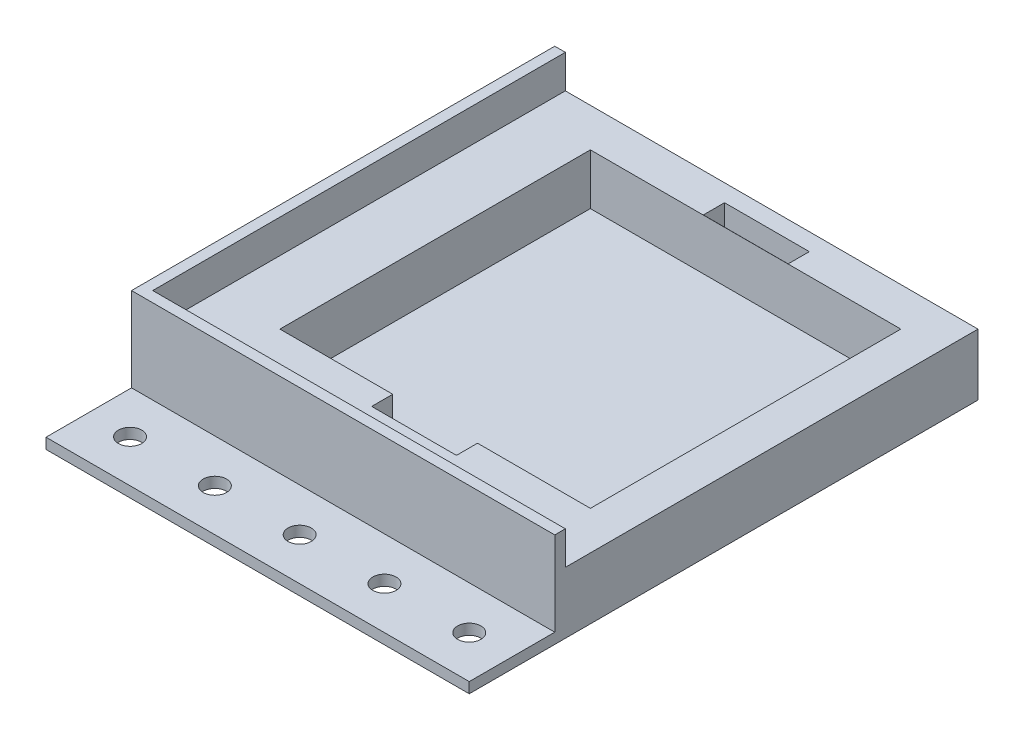
SolidWorks part; units mm, degrees
ref_plane "Front Plane" through (0, 0, 0) normal (0, 0, 1) x (1, 0, 0)
ref_plane "Top Plane" through (0, 0, 0) normal (0, 1, 0) x (1, 0, 0)
ref_plane "Right Plane" through (0, 0, 0) normal (1, 0, 0) x (0, 0, -1)
sketch "Sketch1" plane through (0, 0, 0) normal (0, 1, 0) x (1, 0, 0)
  line L1 (-152.4, -152.4) -> (152.4, -152.4)
  line L2 (-152.4, -152.4) -> (-152.4, 152.4)
  line L3 (-152.4, 152.4) -> (152.4, 152.4)
  line L4 (152.4, -152.4) -> (152.4, 152.4)
  line L5 (104.557, 11.557) -> (11.557, 11.557)
  line L6 (104.557, 11.557) -> (104.557, 104.557)
  line L7 (-11.557, 104.557) -> (-104.557, 104.557)
  line L8 (-11.557, 104.557) -> (-11.557, 11.557)
  line L9 (-11.557, 11.557) -> (-104.557, 11.557)
  line L10 (-104.557, 104.557) -> (-104.557, 11.557)
  line L11 (-11.557, 104.557) -> (-104.557, 11.557) construction
  line L12 (-11.557, 11.557) -> (-104.557, 104.557) construction
  line L13 (104.557, 104.557) -> (11.557, 104.557)
  line L14 (11.557, 11.557) -> (11.557, 104.557)
  line L15 (104.557, 11.557) -> (11.557, 104.557) construction
  line L16 (104.557, 104.557) -> (11.557, 11.557) construction
  line L17 (-104.557, -11.557) -> (-11.557, -11.557)
  line L18 (-104.557, -11.557) -> (-104.557, -104.557)
  line L19 (-104.557, -104.557) -> (-11.557, -104.557)
  line L20 (-11.557, -11.557) -> (-11.557, -104.557)
  line L21 (-104.557, -11.557) -> (-11.557, -104.557) construction
  line L22 (-104.557, -104.557) -> (-11.557, -11.557) construction
  line L23 (11.557, -11.557) -> (104.557, -11.557)
  line L24 (11.557, -11.557) -> (11.557, -104.557)
  line L25 (11.557, -104.557) -> (104.557, -104.557)
  line L26 (104.557, -11.557) -> (104.557, -104.557)
  line L27 (11.557, -11.557) -> (104.557, -104.557) construction
  line L28 (11.557, -104.557) -> (104.557, -11.557) construction
  point P0 (0, 0)
  point P6 (-58.057, 58.057)
  point P11 (58.057, 58.057)
  point P14 (0, 152.4)
  point P16 (-152.4, 0)
  point P18 (-58.057, -58.057)
  point P23 (58.057, -58.057)
  point P28 (-67.5261, -23.6543)
  point P29 (48.5879, -23.6543)
  point P30 (0, 0)
  point P31 (0, 0)
  point P32 (0, 0)
  point P33 (-55.8, 59.6413)
  point P34 (0, 0)
  point P35 (-104.557, 11.557)
  point P36 (0, 0)
  dimension "D1" = 93
  dimension "D2" = 304.8
  dimension "D3" = 23.114
  dimension "D4" = 23.114
extrude "Boss-Extrude1" add sketch "Sketch1" along normal blind 15.24
sketch "Sketch2" plane through (0, 0, 0) normal (0, -1, 0) x (-1, 0, 0)
  line L1 (152.4, -152.4) -> (-152.4, -152.4)
  line L2 (152.4, -152.4) -> (152.4, 152.4)
  line L3 (152.4, 152.4) -> (-152.4, 152.4)
  line L4 (-152.4, -152.4) -> (-152.4, 152.4)
extrude "Boss-Extrude2" add sketch "Sketch2" along normal blind 3.175
sketch "Sketch3" plane through (0, 15.24, 0) normal (0, 1, 0) x (1, 0, 0)
  line L0 (-104.557, 104.557) -> (-104.557, 11.557) construction
  line L1 (-152.4, -152.4) -> (152.4, -152.4)
  line L2 (-152.4, -152.4) -> (-152.4, 152.4)
  line L3 (-152.4, 152.4) -> (152.4, 152.4)
  line L4 (152.4, -152.4) -> (152.4, 152.4)
  line L5 (-123.607, -123.607) -> (123.607, -123.607)
  line L6 (-123.607, -123.607) -> (-123.607, 123.607)
  line L7 (-123.607, 123.607) -> (123.607, 123.607)
  line L8 (123.607, -123.607) -> (123.607, 123.607)
  line L9 (-11.557, 104.557) -> (-104.557, 104.557) construction
  line L10 (11.557, -104.557) -> (104.557, -104.557) construction
  line L11 (104.557, -104.557) -> (104.557, -11.557) construction
  dimension "D1" = 19.05
  dimension "D2" = 19.05
  dimension "D3" = 19.05
  dimension "D4" = 19.05
extrude "Boss-Extrude3" add sketch "Sketch3" along normal blind 10
sketch "Sketch4" plane through (0, 25.24, 0) normal (0, 1, 0) x (1, 0, 0)
  line L0 (123.607, 123.607) -> (-123.607, 123.607) construction
  line L1 (-126.782, 126.782) -> (126.782, 126.782)
  line L2 (-126.782, 126.782) -> (-126.782, -126.782)
  line L3 (-126.782, -126.782) -> (126.782, -126.782)
  line L4 (126.782, 126.782) -> (126.782, -126.782)
  line L5 (-123.607, 123.607) -> (-123.607, -123.607) construction
  line L6 (123.607, -123.607) -> (123.607, 123.607) construction
  line L7 (-123.607, -123.607) -> (123.607, -123.607) construction
  dimension "D1" = 3.175
  dimension "D2" = 3.175
  dimension "D3" = 3.175
  dimension "D4" = 3.175
extrude "Cut-Extrude1" cut sketch "Sketch4" against normal offset from surface (25.24 mm away) 3.175 flip side to cut up to face at (0, -3.175, 0)
sketch "Sketch5" plane through (0, 0, 0) normal (0, 1, 0) x (1, 0, 0)
  line L0 (152.4, -152.4) -> (-152.4, -152.4) construction
  line L1 (-152.4, -152.4) -> (-152.4, 152.4) construction
  circle A0 centre (-139.7, -139.7) radius 3.4925
  circle A1 centre (-114.3, -139.7) radius 3.4925
  circle A2 centre (-88.9, -139.7) radius 3.4925
  circle A3 centre (-63.5, -139.7) radius 3.4925
  circle A4 centre (-38.1, -139.7) radius 3.4925
  circle A5 centre (-12.7, -139.7) radius 3.4925
  circle A6 centre (12.7, -139.7) radius 3.4925
  circle A7 centre (38.1, -139.7) radius 3.4925
  circle A8 centre (63.5, -139.7) radius 3.4925
  circle A9 centre (88.9, -139.7) radius 3.4925
  circle A10 centre (114.3, -139.7) radius 3.4925
  circle A11 centre (139.7, -139.7) radius 3.4925
  circle A12 centre (-139.7, -114.3) radius 3.4925
  circle A13 centre (-139.7, -88.9) radius 3.4925
  circle A14 centre (-139.7, -63.5) radius 3.4925
  circle A15 centre (-139.7, -38.1) radius 3.4925
  circle A16 centre (-139.7, -12.7) radius 3.4925
  circle A17 centre (-139.7, 12.7) radius 3.4925
  circle A18 centre (-139.7, 38.1) radius 3.4925
  circle A19 centre (-139.7, 63.5) radius 3.4925
  circle A20 centre (-139.7, 88.9) radius 3.4925
  circle A21 centre (-139.7, 114.3) radius 3.4925
  circle A22 centre (-139.7, 139.7) radius 3.4925
  circle A23 centre (-114.3, 139.7) radius 3.4925
  circle A24 centre (-88.9, 139.7) radius 3.4925
  circle A25 centre (-63.5, 139.7) radius 3.4925
  circle A26 centre (-38.1, 139.7) radius 3.4925
  circle A27 centre (-12.7, 139.7) radius 3.4925
  circle A28 centre (12.7, 139.7) radius 3.4925
  circle A29 centre (38.1, 139.7) radius 3.4925
  circle A30 centre (63.5, 139.7) radius 3.4925
  circle A31 centre (88.9, 139.7) radius 3.4925
  circle A32 centre (114.3, 139.7) radius 3.4925
  circle A33 centre (139.7, 139.7) radius 3.4925
  circle A34 centre (139.7, 114.3) radius 3.4925
  circle A35 centre (139.7, 88.9) radius 3.4925
  circle A36 centre (139.7, 63.5) radius 3.4925
  circle A37 centre (139.7, 38.1) radius 3.4925
  circle A38 centre (139.7, 12.7) radius 3.4925
  circle A39 centre (139.7, -12.7) radius 3.4925
  circle A40 centre (139.7, -38.1) radius 3.4925
  circle A41 centre (139.7, -63.5) radius 3.4925
  circle A42 centre (139.7, -88.9) radius 3.4925
  circle A43 centre (139.7, -114.3) radius 3.4925
  dimension "D1" = 6.985
  dimension "D2" = 12.7
  dimension "D3" = 12.7
  dimension "D4" = 12
  dimension "D5" = 12
  dimension "D6" = 12
  dimension "D7" = 11
extrude "Cut-Extrude2" cut sketch "Sketch5" against normal through all
sketch "Sketch6" plane through (0, 15.24, 0) normal (0, 1, 0) x (1, 0, 0)
  line L0 (-11.557, 104.557) -> (-104.557, 104.557) construction
  line L1 (-70.757, 104.557) -> (-45.357, 104.557)
  line L2 (-70.757, 104.557) -> (-70.757, 110.907)
  line L3 (-70.757, 110.907) -> (-45.357, 110.907)
  line L4 (-45.357, 104.557) -> (-45.357, 110.907)
  line L5 (-104.557, 104.557) -> (-104.557, 11.557) construction
  line L10 (-104.557, 11.557) -> (-11.557, 11.557) construction
  line L11 (-70.757, 11.557) -> (-45.357, 11.557)
  line L12 (-70.757, 11.557) -> (-70.757, 5.207)
  line L13 (-70.757, 5.207) -> (-45.357, 5.207)
  line L14 (-45.357, 11.557) -> (-45.357, 5.207)
  point P24 (-104.557, 58.057)
  point P27 (-58.057, 11.557)
  point P28 (-58.057, 5.207)
  point P29 (-58.057, 104.557)
  point P30 (-58.057, 110.907)
  dimension "D1" = 25.4
  dimension "D2" = 6.35
extrude "Cut-Extrude3" cut sketch "Sketch6" against normal up to surface (15.24 mm away) up to face at (-58.057, 0, -58.057)
pattern_linear "LPattern1" count 2 spacing 116.078 along (1, 0, 0) count 2 spacing 116.078 along (0, 0, 1) of "Cut-Extrude3"
sketch "Sketch7" plane through (0, 0, -126.782) normal (0, 0, -1) x (-1, 0, 0)
  line L1 (167.8665, -118.5251) -> (-220.3422, -118.5251)
  line L2 (167.8665, -118.5251) -> (167.8665, 67.4439)
  line L3 (167.8665, 67.4439) -> (-220.3422, 67.4439)
  line L4 (-220.3422, -118.5251) -> (-220.3422, 67.4439)
extrude "Cut-Extrude4" cut sketch "Sketch7" along normal through all
sketch "Sketch8" plane through (-126.782, 0, 0) normal (-1, 0, 0) x (0, 0, 1)
  line L1 (-237.2877, -205.7244) -> (307.7637, -205.7244)
  line L2 (-237.2877, -205.7244) -> (-237.2877, 257.5416)
  line L3 (-237.2877, 257.5416) -> (307.7637, 257.5416)
  line L4 (307.7637, -205.7244) -> (307.7637, 257.5416)
extrude "Cut-Extrude5" cut sketch "Sketch8" along normal through all
sketch "Sketch9" plane through (126.782, 0, 0) normal (1, 0, 0) x (0, 0, -1)
  line L1 (-265.9255, 236.578) -> (319.6138, 236.578)
  line L2 (-265.9255, 236.578) -> (-265.9255, -147.0614)
  line L3 (-265.9255, -147.0614) -> (319.6138, -147.0614)
  line L4 (319.6138, 236.578) -> (319.6138, -147.0614)
extrude "Cut-Extrude6" cut sketch "Sketch9" along normal through all
sketch "Sketch10" plane through (0, 0, 0) normal (0, 1, 0) x (1, 0, 0)
  line L1 (-142.1144, 0) -> (0, 0)
  line L2 (-142.1144, 0) -> (-142.1144, -171.898)
  line L3 (-142.1144, -171.898) -> (0, -171.898)
  line L4 (0, 0) -> (0, -171.898)
extrude "Cut-Extrude7" cut sketch "Sketch10" against normal through all both and the other way through all flip side to cut
